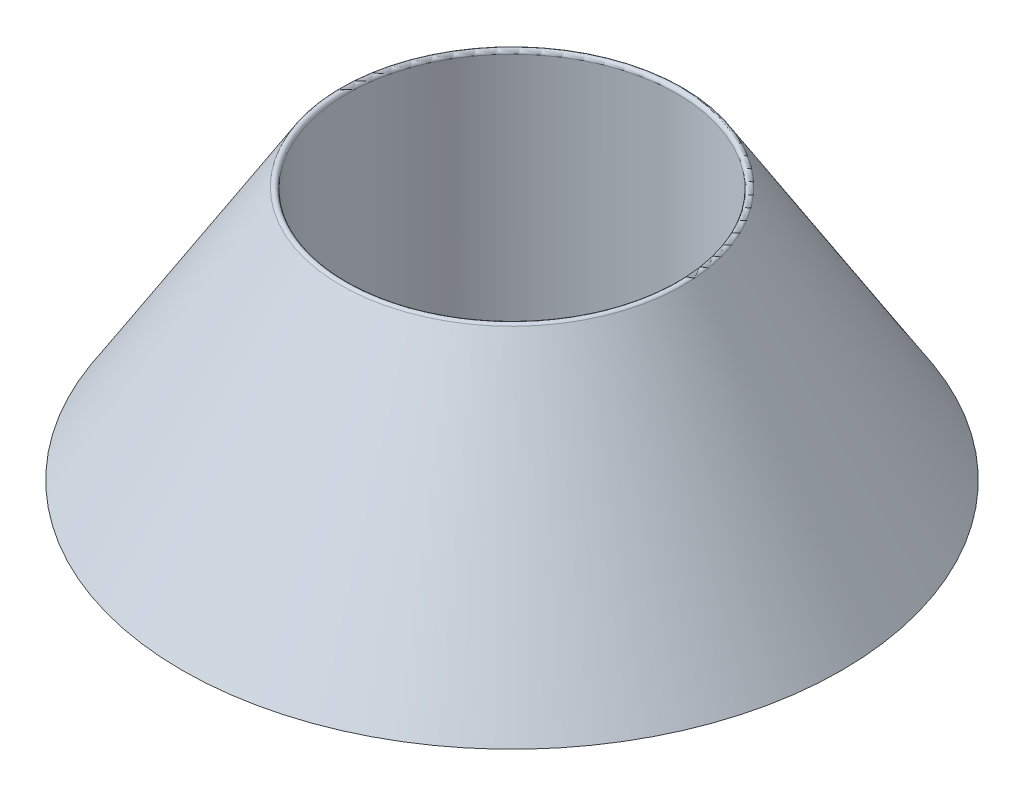
SolidWorks part; units mm, degrees
material "ABS"
ref_plane "Front Plane" through (0, 0, 0) normal (0, 0, 1) x (1, 0, 0)
ref_plane "Top Plane" through (0, 0, 0) normal (0, 1, 0) x (1, 0, 0)
ref_plane "Right Plane" through (0, 0, 0) normal (1, 0, 0) x (0, 0, -1)
sketch "Sketch2" plane through (0, 0, 0) normal (0, 0, 1) x (1, 0, 0)
  line L0 (0, 0) -> (5, 0)
  line L1 (0, 0) -> (0, 4)
  line L2 (0, 4) -> (2.5, 4)
  line L3 (2.5, 4) -> (2.5, 0)
  line L4 (2.5, 4) -> (5, 0)
revolve "Revolve1" add sketch "Sketch2" angle 360 about L1
fillet "Fillet1" radius 0.05 1 edges at (0, 4, -2.5)
